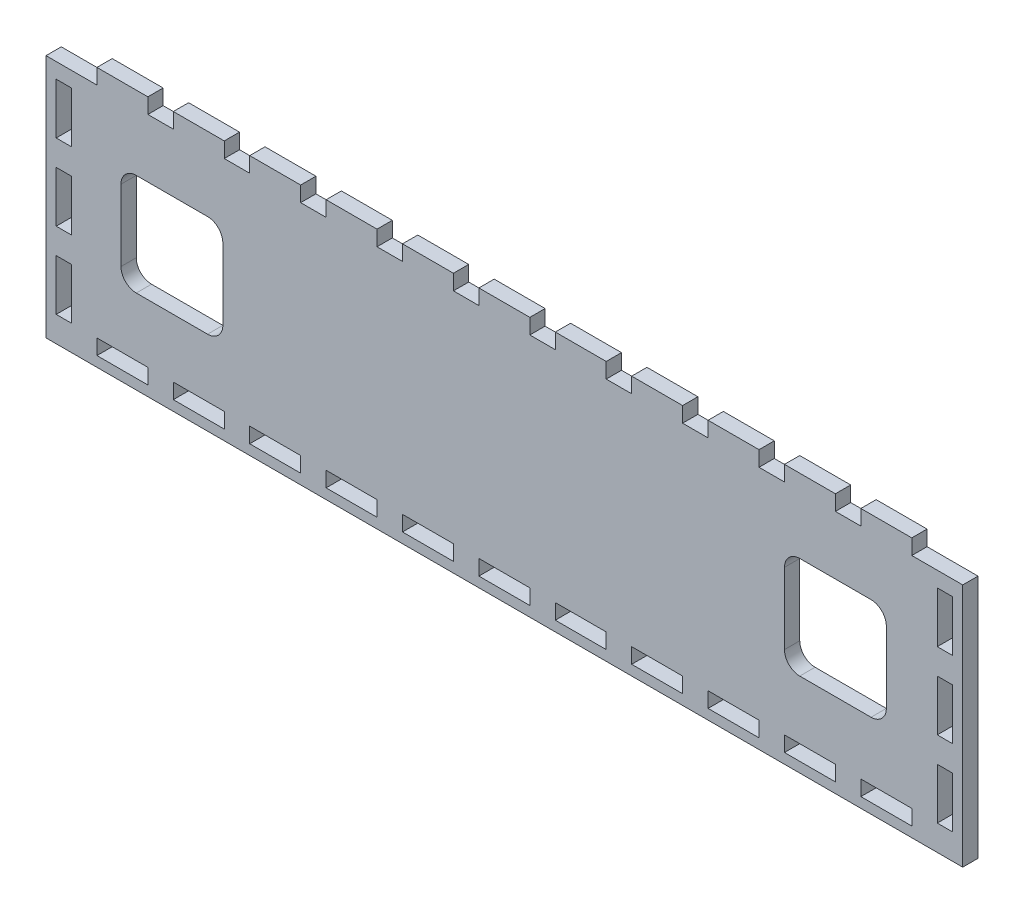
SolidWorks part; units mm, degrees
material "轻木"
ref_plane "前视基准面" through (0, 0, 0) normal (0, 0, 1) x (1, 0, 0)
ref_plane "上视基准面" through (0, 0, 0) normal (0, 1, 0) x (1, 0, 0)
ref_plane "右视基准面" through (0, 0, 0) normal (1, 0, 0) x (0, 0, -1)
sketch "草图1" plane through (0, 0, 0) normal (0, 0, 1) x (1, 0, 0)
  line L0 (-84.8613, 4.9161) -> (-84.8613, -5.0839)
  line L1 (-89.8613, 22.9161) -> (-79.8613, 22.9161)
  line L2 (-89.8613, 22.9161) -> (-89.8613, -25.0839)
  line L3 (-89.8613, -25.0839) -> (90.1387, -25.0839)
  line L4 (90.1387, 22.9161) -> (90.1387, -25.0839)
  line L5 (-89.8613, 22.9161) -> (90.1387, -25.0839) construction
  line L6 (-89.8613, -25.0839) -> (90.1387, 22.9161) construction
  line L7 (-84.8613, 19.9161) -> (-87.8613, 19.9161)
  line L8 (-84.8613, 19.9161) -> (-84.8613, 9.9161)
  line L9 (-84.8613, 9.9161) -> (-87.8613, 9.9161)
  line L10 (-87.8613, 19.9161) -> (-87.8613, 9.9161)
  line L11 (-84.8613, 4.9161) -> (-87.8613, 4.9161)
  line L12 (-87.8613, 4.9161) -> (-87.8613, -5.0839)
  line L13 (-84.8613, -5.0839) -> (-87.8613, -5.0839)
  line L14 (-84.8613, -10.0839) -> (-84.8613, -20.0839)
  line L15 (-84.8613, -10.0839) -> (-87.8613, -10.0839)
  line L16 (-87.8613, -10.0839) -> (-87.8613, -20.0839)
  line L17 (-84.8613, -20.0839) -> (-87.8613, -20.0839)
  line L18 (-64.8613, 22.9161) -> (-64.8613, 25.9161)
  line L19 (-79.8613, 22.9161) -> (-79.8613, 25.9161)
  line L20 (-79.8613, 25.9161) -> (-69.8613, 25.9161)
  line L21 (-69.8613, 22.9161) -> (-69.8613, 25.9161)
  line L22 (-54.8613, 22.9161) -> (-54.8613, 25.9161)
  line L23 (-64.8613, 25.9161) -> (-54.8613, 25.9161)
  line L24 (-49.8613, 22.9161) -> (-49.8613, 25.9161)
  line L25 (-39.8613, 22.9161) -> (-39.8613, 25.9161)
  line L26 (-49.8613, 25.9161) -> (-39.8613, 25.9161)
  line L27 (-34.8613, 22.9161) -> (-34.8613, 25.9161)
  line L28 (-24.8613, 22.9161) -> (-24.8613, 25.9161)
  line L29 (-34.8613, 25.9161) -> (-24.8613, 25.9161)
  line L30 (-19.8613, 22.9161) -> (-19.8613, 25.9161)
  line L31 (-9.8613, 22.9161) -> (-9.8613, 25.9161)
  line L32 (-19.8613, 25.9161) -> (-9.8613, 25.9161)
  line L33 (-4.8613, 22.9161) -> (-4.8613, 25.9161)
  line L34 (5.1387, 22.9161) -> (5.1387, 25.9161)
  line L35 (-4.8613, 25.9161) -> (5.1387, 25.9161)
  line L36 (10.1387, 22.9161) -> (10.1387, 25.9161)
  line L37 (20.1387, 22.9161) -> (20.1387, 25.9161)
  line L38 (10.1387, 25.9161) -> (20.1387, 25.9161)
  line L39 (25.1387, 22.9161) -> (25.1387, 25.9161)
  line L40 (35.1387, 22.9161) -> (35.1387, 25.9161)
  line L41 (25.1387, 25.9161) -> (35.1387, 25.9161)
  line L42 (40.1387, 22.9161) -> (40.1387, 25.9161)
  line L43 (50.1387, 22.9161) -> (50.1387, 25.9161)
  line L44 (40.1387, 25.9161) -> (50.1387, 25.9161)
  line L45 (55.1387, 22.9161) -> (55.1387, 25.9161)
  line L46 (65.1387, 22.9161) -> (65.1387, 25.9161)
  line L47 (55.1387, 25.9161) -> (65.1387, 25.9161)
  line L48 (70.1387, 22.9161) -> (70.1387, 25.9161)
  line L49 (80.1387, 22.9161) -> (80.1387, 25.9161)
  line L50 (70.1387, 25.9161) -> (80.1387, 25.9161)
  line L51 (85.1387, -10.0839) -> (88.1387, -10.0839)
  line L52 (88.1387, -10.0839) -> (88.1387, -20.0839)
  line L53 (85.1387, -20.0839) -> (88.1387, -20.0839)
  line L54 (85.1387, -10.0839) -> (85.1387, -20.0839)
  line L55 (85.1387, 4.9161) -> (88.1387, 4.9161)
  line L56 (88.1387, 4.9161) -> (88.1387, -5.0839)
  line L57 (85.1387, -5.0839) -> (88.1387, -5.0839)
  line L58 (85.1387, 4.9161) -> (85.1387, -5.0839)
  line L59 (85.1387, 9.9161) -> (88.1387, 9.9161)
  line L60 (88.1387, 19.9161) -> (88.1387, 9.9161)
  line L61 (85.1387, 19.9161) -> (88.1387, 19.9161)
  line L62 (85.1387, 19.9161) -> (85.1387, 9.9161)
  line L63 (-54.8613, -23.0839) -> (-54.8613, -20.0839)
  line L64 (-69.8613, -23.0839) -> (-79.8613, -23.0839)
  line L65 (-69.8613, -23.0839) -> (-69.8613, -20.0839)
  line L66 (-69.8613, -20.0839) -> (-79.8613, -20.0839)
  line L67 (-79.8613, -23.0839) -> (-79.8613, -20.0839)
  line L68 (-54.8613, -23.0839) -> (-64.8613, -23.0839)
  line L69 (-64.8613, -23.0839) -> (-64.8613, -20.0839)
  line L70 (-54.8613, -20.0839) -> (-64.8613, -20.0839)
  line L71 (-39.8613, -23.0839) -> (-39.8613, -20.0839)
  line L72 (-39.8613, -23.0839) -> (-49.8613, -23.0839)
  line L73 (-49.8613, -23.0839) -> (-49.8613, -20.0839)
  line L74 (-39.8613, -20.0839) -> (-49.8613, -20.0839)
  line L75 (-24.8613, -23.0839) -> (-24.8613, -20.0839)
  line L76 (-24.8613, -23.0839) -> (-34.8613, -23.0839)
  line L77 (-34.8613, -23.0839) -> (-34.8613, -20.0839)
  line L78 (-24.8613, -20.0839) -> (-34.8613, -20.0839)
  line L79 (-9.8613, -23.0839) -> (-9.8613, -20.0839)
  line L80 (-9.8613, -23.0839) -> (-19.8613, -23.0839)
  line L81 (-19.8613, -23.0839) -> (-19.8613, -20.0839)
  line L82 (-9.8613, -20.0839) -> (-19.8613, -20.0839)
  line L83 (5.1387, -23.0839) -> (5.1387, -20.0839)
  line L84 (5.1387, -23.0839) -> (-4.8613, -23.0839)
  line L85 (-4.8613, -23.0839) -> (-4.8613, -20.0839)
  line L86 (5.1387, -20.0839) -> (-4.8613, -20.0839)
  line L87 (20.1387, -23.0839) -> (20.1387, -20.0839)
  line L88 (20.1387, -23.0839) -> (10.1387, -23.0839)
  line L89 (10.1387, -23.0839) -> (10.1387, -20.0839)
  line L90 (20.1387, -20.0839) -> (10.1387, -20.0839)
  line L91 (35.1387, -23.0839) -> (35.1387, -20.0839)
  line L92 (35.1387, -23.0839) -> (25.1387, -23.0839)
  line L93 (25.1387, -23.0839) -> (25.1387, -20.0839)
  line L94 (35.1387, -20.0839) -> (25.1387, -20.0839)
  line L95 (50.1387, -23.0839) -> (50.1387, -20.0839)
  line L96 (50.1387, -23.0839) -> (40.1387, -23.0839)
  line L97 (40.1387, -23.0839) -> (40.1387, -20.0839)
  line L98 (50.1387, -20.0839) -> (40.1387, -20.0839)
  line L99 (65.1387, -23.0839) -> (65.1387, -20.0839)
  line L100 (65.1387, -23.0839) -> (55.1387, -23.0839)
  line L101 (55.1387, -23.0839) -> (55.1387, -20.0839)
  line L102 (65.1387, -20.0839) -> (55.1387, -20.0839)
  line L103 (80.1387, -23.0839) -> (80.1387, -20.0839)
  line L104 (80.1387, -23.0839) -> (70.1387, -23.0839)
  line L105 (70.1387, -23.0839) -> (70.1387, -20.0839)
  line L106 (80.1387, -20.0839) -> (70.1387, -20.0839)
  line L107 (-69.8613, 22.9161) -> (-64.8613, 22.9161)
  line L108 (-54.8613, 22.9161) -> (-49.8613, 22.9161)
  line L109 (-39.8613, 22.9161) -> (-34.8613, 22.9161)
  line L110 (-24.8613, 22.9161) -> (-19.8613, 22.9161)
  line L111 (-9.8613, 22.9161) -> (-4.8613, 22.9161)
  line L112 (5.1387, 22.9161) -> (10.1387, 22.9161)
  line L113 (20.1387, 22.9161) -> (25.1387, 22.9161)
  line L114 (35.1387, 22.9161) -> (40.1387, 22.9161)
  line L115 (50.1387, 22.9161) -> (55.1387, 22.9161)
  line L116 (65.1387, 22.9161) -> (70.1387, 22.9161)
  line L117 (80.1387, 22.9161) -> (90.1387, 22.9161)
  point P0 (0.1387, -1.0839)
  dimension "D1" = 48
  dimension "D2" = 180
  dimension "D3" = 10
  dimension "D4" = 3
  dimension "D5" = 3
  dimension "D6" = 2
  dimension "D7" = 3
  dimension "D8" = 10
  dimension "D9" = 10
  dimension "D10" = 10
  dimension "D11" = 3
  dimension "D12" = 2
  dimension "D13" = 10
extrude "凸台-拉伸1" add sketch "草图1" along normal blind 3
sketch "草图2" plane through (0, 0, 3) normal (0, 0, 1) x (1, 0, 0)
  line L0 (85.1387, 4.9161) -> (85.1387, -5.0839) construction
  line L1 (55.1387, 11.4135) -> (75.1387, 11.4135)
  line L2 (55.1387, 11.4135) -> (55.1387, -8.5865)
  line L3 (55.1387, -8.5865) -> (75.1387, -8.5865)
  line L4 (75.1387, 11.4135) -> (75.1387, -8.5865)
  line L5 (55.1387, 11.4135) -> (75.1387, -8.5865) construction
  line L6 (55.1387, -8.5865) -> (75.1387, 11.4135) construction
  line L7 (0, -7.15) -> (0, 7.15) construction
  line L8 (-55.1387, -8.5865) -> (-75.1387, -8.5865)
  line L9 (-75.1387, 11.4135) -> (-75.1387, -8.5865)
  line L10 (-55.1387, 11.4135) -> (-75.1387, 11.4135)
  line L11 (-55.1387, 11.4135) -> (-55.1387, -8.5865)
  point P0 (65.1387, 1.4135)
  point P7 (85.1387, -0.0839)
  dimension "D1" = 20
  dimension "D2" = 20
  dimension "D3" = 10
extrude "切除-拉伸1" cut sketch "草图2" against normal blind 10
fillet "圆角1" radius 3 8 edges at (55.1387, 11.4135, 1.5) (75.1387, 11.4135, 1.5) (75.1387, -8.5865, 1.5) (55.1387, -8.5865, 1.5) (-75.1387, -8.5865, 1.5) (-55.1387, -8.5865, 1.5) (-55.1387, 11.4135, 1.5) (-75.1387, 11.4135, 1.5)
